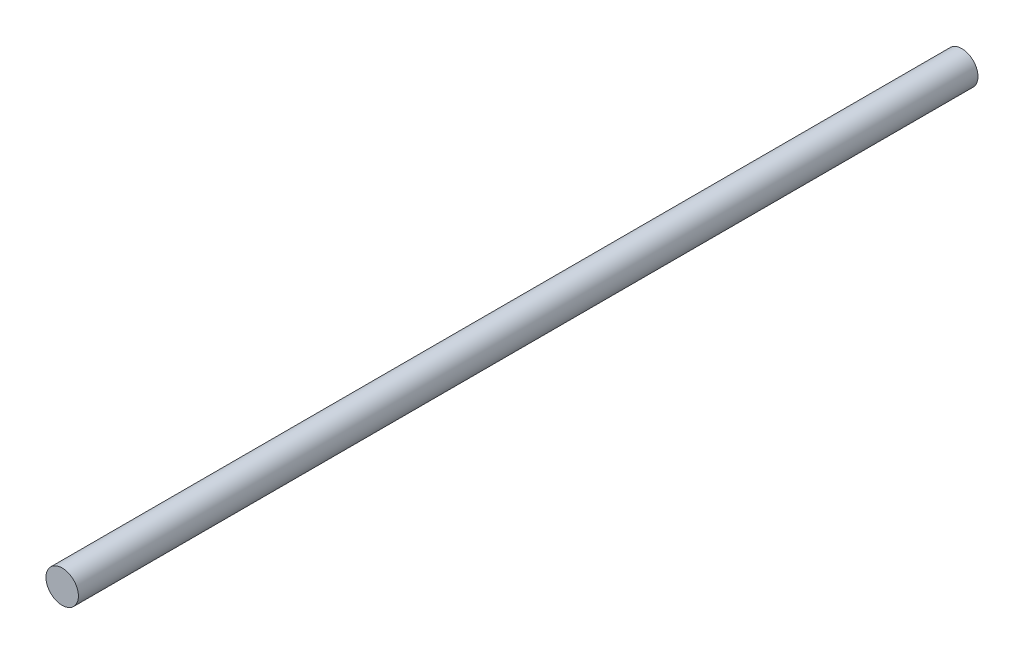
SolidWorks part; units mm, degrees
ref_plane "Front Plane" through (0, 0, 0) normal (0, 0, 1) x (1, 0, 0)
ref_plane "Top Plane" through (0, 0, 0) normal (0, 1, 0) x (1, 0, 0)
ref_plane "Right Plane" through (0, 0, 0) normal (1, 0, 0) x (0, 0, -1)
sketch "Sketch1" plane through (0, 0, 0) normal (0, 0, 1) x (1, 0, 0)
  circle A0 centre (0, 0) radius 4
extrude "Rod" add sketch "Sketch1" along normal blind 222
